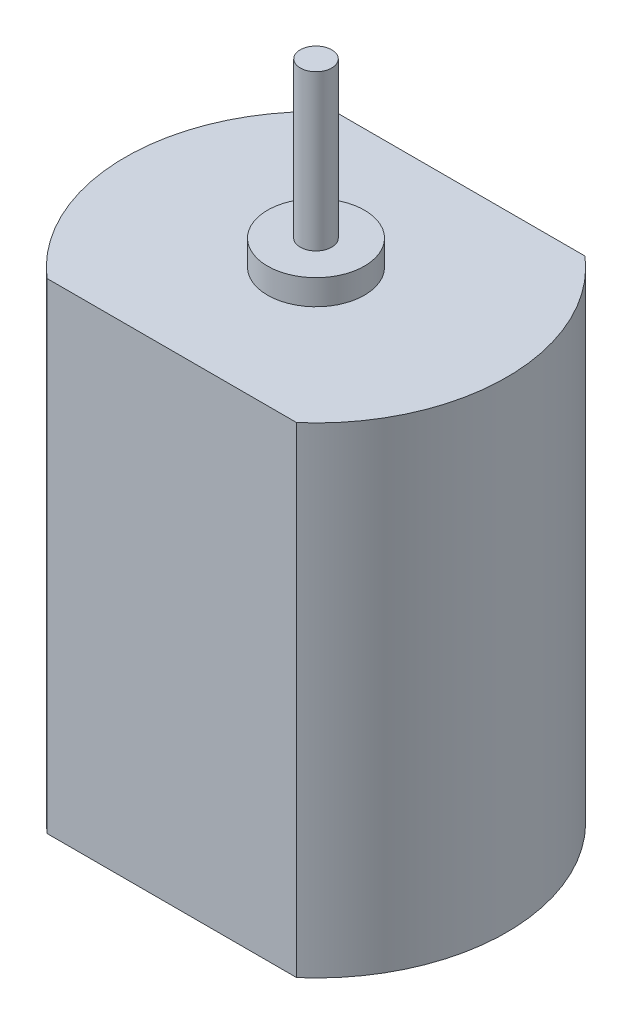
SolidWorks part; units mm, degrees
ref_plane "Front Plane" through (0, 0, 0) normal (0, 0, 1) x (1, 0, 0)
ref_plane "Top Plane" through (0, 0, 0) normal (0, 1, 0) x (1, 0, 0)
ref_plane "Right Plane" through (0, 0, 0) normal (1, 0, 0) x (0, 0, -1)
sketch "Sketch2" plane through (0, 0, 0) normal (0, 1, 0) x (1, 0, 0)
  line L1 (0, 12.1) -> (0, -12.1) construction
  line L3 (-7.9175, 9.15) -> (7.9175, 9.15)
  line L4 (-7.9175, -9.15) -> (7.9175, -9.15)
  arc A0 (-7.9175, 9.15) -> (-7.9175, -9.15) centre (0, 0) ccw
  arc A1 (7.9175, -9.15) -> (7.9175, 9.15) centre (0, 0) ccw
  dimension "D1" = 24.2
  dimension "D2" = 18.3
  dimension "D3" = 15.8351
extrude "Boss-Extrude1" add sketch "Sketch2" along normal blind 30.5
sketch "Sketch3" plane through (0, 30.5, 0) normal (0, 1, 0) x (1, 0, 0)
  circle A0 centre (0, 0) radius 3.075
  dimension "D1" = 6.15
extrude "Boss-Extrude2" add sketch "Sketch3" along normal blind 1.6
sketch "Sketch4" plane through (0, 32.1, 0) normal (0, 1, 0) x (1, 0, 0)
  circle A0 centre (0, 0) radius 1
  dimension "D1" = 2
extrude "Boss-Extrude3" add sketch "Sketch4" along normal blind 9.85
sketch "Sketch5" plane through (0, 0, 0) normal (0, -1, 0) x (1, 0, 0)
  circle A0 centre (0, 0) radius 4.25
  dimension "D1" = 8.5
extrude "Boss-Extrude4" add sketch "Sketch5" along normal blind 2
